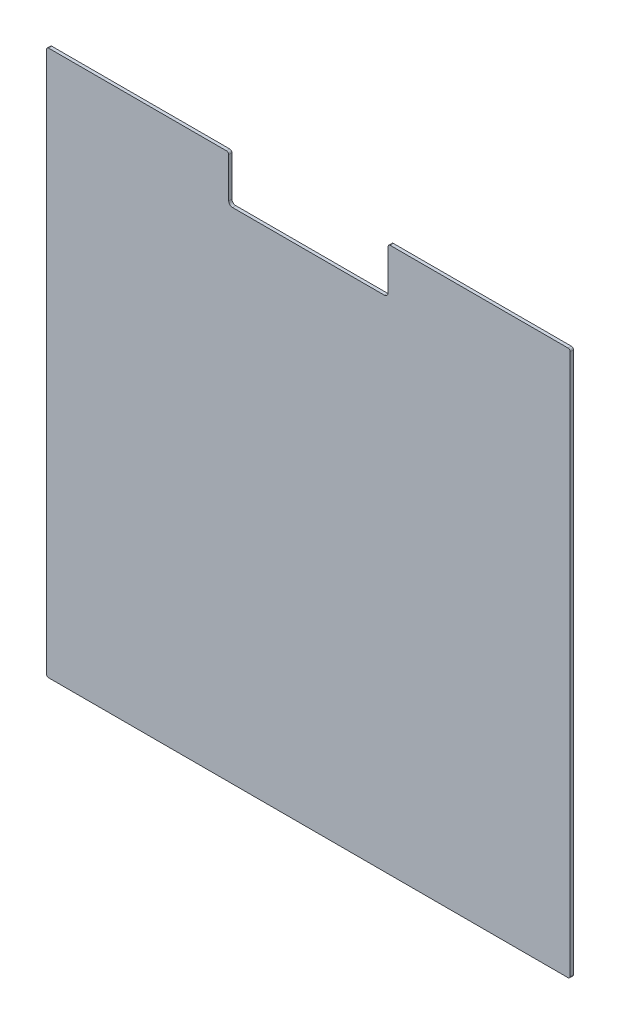
SolidWorks part; units mm, degrees
ref_plane "Front Plane" through (0, 0, 0) normal (0, 0, 1) x (1, 0, 0)
ref_plane "Top Plane" through (0, 0, 0) normal (0, 1, 0) x (1, 0, 0)
ref_plane "Right Plane" through (0, 0, 0) normal (1, 0, 0) x (0, 0, -1)
sketch "Model" plane through (0, 0, 0) normal (0, 0, 1) x (1, 0, 0)
  line L0 (76.4774, -141.5) -> (-402.5226, -141.5)
  line L1 (-404.5226, -139.5) -> (-404.5226, 359.5)
  line L2 (-402.5226, 361.5) -> (-238.4997, 361.5)
  line L3 (-236.4997, 359.5) -> (-236.4997, 322.5)
  line L4 (-232.9997, 319) -> (-92.9997, 319)
  line L5 (-89.4997, 322.5) -> (-89.4997, 359.5)
  line L6 (-87.4997, 361.5) -> (76.4774, 361.5)
  line L7 (78.4774, 359.5) -> (78.4774, -139.5)
  arc A0 (76.4774, -141.5) -> (78.4774, -139.5) centre (76.4774, -139.5) ccw
  arc A1 (-404.5226, -139.5) -> (-402.5226, -141.5) centre (-402.5226, -139.5) ccw
  arc A2 (-402.5226, 361.5) -> (-404.5226, 359.5) centre (-402.5226, 359.5) ccw
  arc A3 (-236.4997, 359.5) -> (-238.4997, 361.5) centre (-238.4997, 359.5) ccw
  arc A4 (-236.4997, 322.5) -> (-232.9997, 319) centre (-232.9997, 322.5) ccw
  arc A5 (-92.9997, 319) -> (-89.4997, 322.5) centre (-92.9997, 322.5) ccw
  arc A6 (-87.4997, 361.5) -> (-89.4997, 359.5) centre (-87.4997, 359.5) ccw
  arc A7 (78.4774, 359.5) -> (76.4774, 361.5) centre (76.4774, 359.5) ccw
extrude "Boss-Extrude1" add sketch "Model" along normal blind 3
